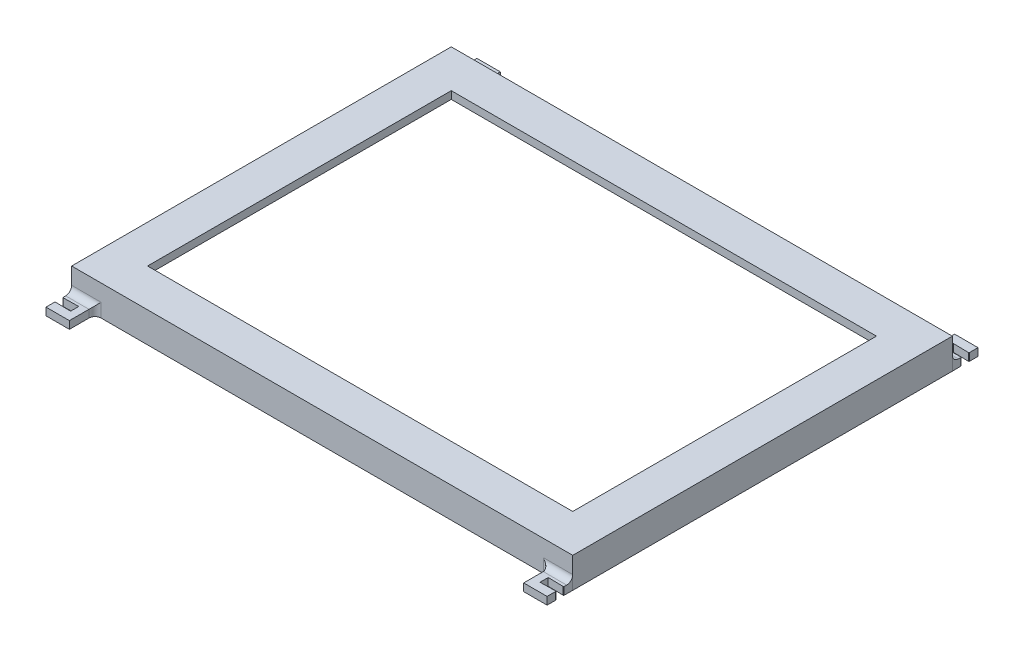
SolidWorks part; units mm, degrees
ref_plane "Front Plane" through (0, 0, 0) normal (0, 0, 1) x (1, 0, 0)
ref_plane "Top Plane" through (0, 0, 0) normal (0, 1, 0) x (1, 0, 0)
ref_plane "Right Plane" through (0, 0, 0) normal (1, 0, 0) x (0, 0, -1)
sketch "Sketch1" plane through (0, 9.525, 0) normal (0, 1, 0) x (1, 0, 0)
  line L12 (261.9455, 40.3596) -> (84.1455, 40.3596)
  line L13 (84.1455, 40.3596) -> (84.1455, -86.6404)
  line L14 (84.1455, -86.6404) -> (261.9455, -86.6404)
  line L15 (261.9455, -86.6404) -> (261.9455, 40.3596)
  line L16 (277.8205, 56.2346) -> (68.2705, 56.2346)
  line L17 (277.8205, -102.5154) -> (277.8205, 56.2346)
  line L18 (68.2705, -102.5154) -> (277.8205, -102.5154)
  line L19 (68.2705, 56.2346) -> (68.2705, -102.5154)
  line L20 (277.8205, 56.2346) -> (68.2705, 56.2346)
  line L21 (277.8205, -102.5154) -> (277.8205, 56.2346)
  line L22 (68.2705, -102.5154) -> (277.8205, -102.5154)
  line L23 (68.2705, 56.2346) -> (68.2705, -102.5154)
  dimension "D2" = 15.875
  dimension "D1" = 3.175
extrude "FrontFace" add sketch "Sketch1" along normal blind 3.175
sketch "Sketch3" plane through (0, 9.525, 0) normal (0, -1, 0) x (1, 0, 0)
  line L4 (277.8205, -56.2346) -> (277.8205, 102.5154)
  line L5 (277.8205, 102.5154) -> (68.2705, 102.5154)
  line L6 (68.2705, 102.5154) -> (68.2705, -56.2346)
  line L7 (68.2705, -56.2346) -> (277.8205, -56.2346)
  line L8 (277.8205, -56.2346) -> (277.8205, 102.5154)
  line L9 (277.8205, 102.5154) -> (68.2705, 102.5154)
  line L10 (68.2705, 102.5154) -> (68.2705, -56.2346)
  line L11 (68.2705, -56.2346) -> (277.8205, -56.2346)
  line L12 (71.1915, 99.5944) -> (71.1915, -53.3136)
  line L17 (71.1915, -53.3136) -> (274.8995, -53.3136)
  line L18 (274.8995, 99.5944) -> (274.8995, -53.3136)
  line L19 (71.1915, 99.5944) -> (274.8995, 99.5944)
  dimension "D2" = 2.921
extrude "SideShell" add sketch "Sketch3" along normal up to surface (9.525 mm away)
sketch "Sketch9" plane through (0, 0, 0) normal (0, -1, 0) x (1, 0, 0)
  line L0 (277.8205, 102.5154) -> (268.0366, 102.5154)
  line L1 (68.2705, 102.5154) -> (277.8205, 102.5154) construction
  line L2 (268.0366, 102.5154) -> (268.0366, 113.2376)
  line L3 (268.0366, 113.2376) -> (277.8205, 113.2376)
  line L4 (277.8205, 113.2376) -> (277.8205, 109.7211)
  line L5 (277.5616, 109.4672) -> (271.2116, 109.591)
  line L6 (271.2116, 109.591) -> (271.2116, 106.162)
  line L7 (271.2116, 106.162) -> (277.5204, 106.2826)
  line L8 (277.7792, 106.0316) -> (277.8205, 102.5154)
  line L9 (173.0455, 102.5154) -> (173.0455, -56.2346) construction
  line L12 (277.8205, -56.2346) -> (68.2705, -56.2346) construction
  line L39 (68.2705, 23.1404) -> (277.8205, 23.1404) construction
  line L40 (68.2705, -56.2346) -> (68.2705, 102.5154) construction
  line L41 (277.8205, 102.5154) -> (277.8205, -56.2346) construction
  line L42 (277.7792, -59.7509) -> (277.8205, -56.2346)
  line L43 (271.2116, -59.8812) -> (277.5204, -60.0018)
  line L44 (271.2116, -63.3102) -> (271.2116, -59.8812)
  line L45 (277.5616, -63.1865) -> (271.2116, -63.3102)
  line L46 (277.8205, -66.9569) -> (277.8205, -63.4404)
  line L47 (268.0366, -66.9569) -> (277.8205, -66.9569)
  line L48 (268.0366, -56.2346) -> (268.0366, -66.9569)
  line L49 (277.8205, -56.2346) -> (268.0366, -56.2346)
  line L50 (68.2705, -56.2346) -> (78.0545, -56.2346)
  line L51 (78.0545, -56.2346) -> (78.0545, -66.9569)
  line L52 (78.0545, -66.9569) -> (68.2705, -66.9569)
  line L53 (68.2705, -66.9569) -> (68.2705, -63.4404)
  line L54 (68.5295, -63.1865) -> (74.8795, -63.3102)
  line L55 (74.8795, -63.3102) -> (74.8795, -59.8812)
  line L56 (74.8795, -59.8812) -> (68.5707, -60.0018)
  line L57 (68.3118, -59.7509) -> (68.2705, -56.2346)
  line L58 (68.3118, 106.0316) -> (68.2705, 102.5154)
  line L59 (74.8795, 106.162) -> (68.5707, 106.2826)
  line L60 (74.8795, 109.591) -> (74.8795, 106.162)
  line L61 (68.5295, 109.4672) -> (74.8795, 109.591)
  line L62 (68.2705, 113.2376) -> (68.2705, 109.7211)
  line L63 (78.0545, 113.2376) -> (68.2705, 113.2376)
  line L64 (78.0545, 102.5154) -> (78.0545, 113.2376)
  line L65 (68.2705, 102.5154) -> (78.0545, 102.5154)
  arc A0 (277.5204, 106.2826) -> (277.7792, 106.0316) centre (277.5252, 106.0286) cw
  arc A1 (277.8205, 109.7211) -> (277.5616, 109.4672) centre (277.5665, 109.7211) cw
  arc A8 (277.8205, -63.4404) -> (277.5616, -63.1865) centre (277.5665, -63.4404) ccw
  arc A9 (277.5204, -60.0018) -> (277.7792, -59.7509) centre (277.5252, -59.7479) ccw
  arc A10 (68.5707, -60.0018) -> (68.3118, -59.7509) centre (68.5658, -59.7479) cw
  arc A11 (68.2705, -63.4404) -> (68.5295, -63.1865) centre (68.5245, -63.4404) cw
  arc A12 (68.2705, 109.7211) -> (68.5295, 109.4672) centre (68.5245, 109.7211) ccw
  arc A13 (68.5707, 106.2826) -> (68.3118, 106.0316) centre (68.5658, 106.0286) ccw
  point P14 (277.7762, 106.2875)
  point P17 (277.8205, 109.4621)
  point P18 (271.2116, 107.8765)
  point P19 (268.0366, 107.8765)
  point P41 (277.8205, -63.1814)
  point P42 (277.7762, -60.0067)
  point P67 (68.3149, -60.0067)
  point P68 (68.2705, -63.1814)
  point P69 (68.2705, 109.4621)
  point P70 (68.3149, 106.2875)
  dimension "D3" = 0.254
  dimension "D1" = 3.175
  dimension "D2" = 3.429
  dimension "D4" = 6.35
  dimension "D5" = 3.175
extrude "BottomSupportLock" add sketch "Sketch9" against normal blind 3.175
fillet "Fillet1" radius 2.54 8 edges at (268.0366, 1.5875, 102.5154) (272.9285, 3.175, 102.5154) (268.0366, 1.5875, -56.2346) (272.9285, 3.175, -56.2346) (78.0545, 1.5875, -56.2346) (73.1625, 3.175, -56.2346) (78.0545, 1.5875, 102.5154) (73.1625, 3.175, 102.5154)
equation "\"ShellWallThickness\"=0.115"
equation "\"D2@Sketch3\"=\"ShellWallThickness\""
equation "\"ShellOverlap\"=0.625"
equation "\"D2@Sketch1\"=\"ShellOverlap\""
